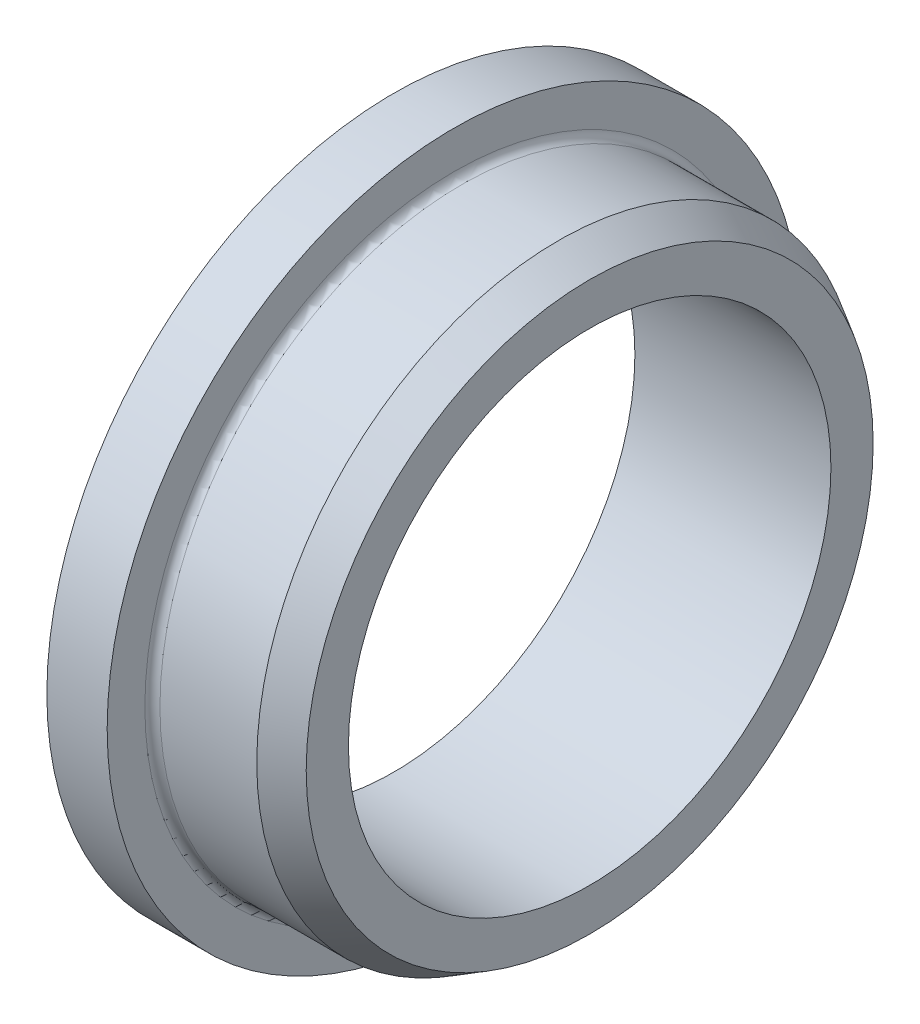
SolidWorks part; units mm, degrees
material "PA Type 6"
ref_plane "Front Plane" through (0, 0, 0) normal (0, 0, 1) x (1, 0, 0)
ref_plane "Top Plane" through (0, 0, 0) normal (0, 1, 0) x (1, 0, 0)
ref_plane "Right Plane" through (0, 0, 0) normal (1, 0, 0) x (0, 0, -1)
sketch "Sketch1" plane through (0, 0, 0) normal (0, 0, 1) x (1, 0, 0)
  line L0 (0, 16) -> (13, 16)
  line L1 (13, 16) -> (13, 20)
  line L2 (13, 20) -> (4, 20)
  line L3 (4, 20) -> (4, 23)
  line L4 (4, 23) -> (0, 23)
  line L5 (0, 23) -> (0, 16)
  line L6 (0, 0) -> (36.921, 0) construction
  dimension "D1" = 16
  dimension "D2" = 20
  dimension "D3" = 23
  dimension "D4" = 4
  dimension "D5" = 13
revolve "Revolve1" add sketch "Sketch1" angle 360 about L6
fillet "Fillet1" radius 0.5 1 edges at (4, 0, 20)
chamfer "Chamfer1" distance 1.2 angle 60 1 edges at (13, 0, 20)
